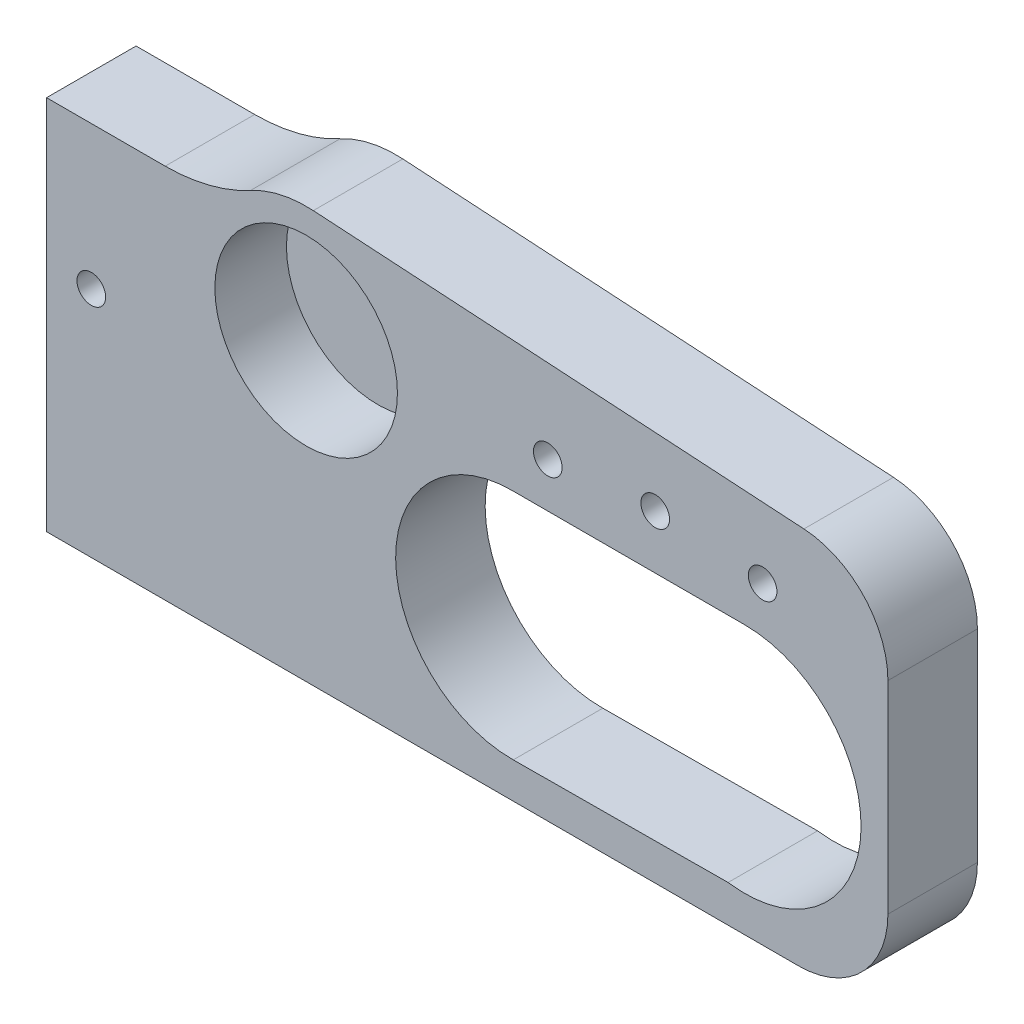
SolidWorks part; units mm, degrees
ref_plane "Front Plane" through (0, 0, 0) normal (1, 0, 0) x (0, 1, 0)
ref_plane "Top Plane" through (0, 0, 0) normal (0, 0, 1) x (0, 1, 0)
ref_plane "Right Plane" through (0, 0, 0) normal (0, 1, 0) x (-1, 0, 0)
sketch "Sketch1" plane through (0, 0, 0) normal (0, 0, 1) x (0, 1, 0)
  line L0 (12.9142, -18.3709) -> (14.6113, 9.0364)
  line L1 (7.9237, -23.0618) -> (-3.3763, -23.0618)
  line L4 (-8.3763, 23.9382) -> (12.6237, 23.9382)
  line L5 (12.6237, 23.9382) -> (12.6237, 17.3122)
  line L7 (-6.3763, -2.0618) -> (-6.2989, -16.0618)
  line L8 (6.6237, -15.0618) -> (6.6237, -2.0618)
  line L10 (-8.3763, 23.9382) -> (-8.3763, -18.0618)
  arc A2 (14.6113, 9.0364) -> (13.8358, 12.54) centre (8.1237, 9.4382) ccw
  arc A3 (12.6237, 17.3122) -> (13.8358, 12.54) centre (22.6237, 17.3122) ccw
  arc A4 (-8.3763, -18.0618) -> (-3.3763, -23.0618) centre (-3.3763, -18.0618) ccw
  arc A5 (7.9237, -23.0618) -> (12.9142, -18.3709) centre (7.9237, -18.0618) ccw
  circle A8 centre (4.6237, 21.4382) radius 0.8
  circle A9 centre (9.1237, -4.0618) radius 0.8
  circle A10 centre (9.6237, -10.0618) radius 0.8
  circle A11 centre (9.1237, -16.0618) radius 0.8
  arc A12 (6.6237, -2.0618) -> (-6.3759, -2.1337) centre (0.1237, -2.0618) ccw
  arc A13 (-6.3096, -14.1329) -> (6.6237, -15.0618) centre (0.1237, -15.0618) ccw
  circle A16 centre (8.1237, 9.4382) radius 5.1
  dimension "D8" = 2.5
  dimension "D1" = 21
  dimension "D2" = 42
  dimension "D3" = 27.4598
  dimension "D4" = 11.3
  dimension "D5" = 2.5
  dimension "D6" = 2.5
  dimension "D7" = 3
extrude "Boss-Extrude1" add sketch "Sketch1" along normal blind 5
sketch "Sketch2" plane through (-23.9382, 0, 0) normal (-1, 0, 0) x (0, -1, 0)
  line L0 (-12.6237, 2.5) -> (-9.6237, 2.5) construction
  line L1 (-12.6237, 5) -> (-12.6237, 0) construction
  line L2 (8.3763, 5) -> (8.3763, 0) construction
  circle A0 centre (-9.6237, 2.5) radius 1.25
  circle A1 centre (5.3763, 2.5) radius 1.25
  dimension "D2" = 3
  dimension "D3" = 2.5
  dimension "D4" = 2.5
  dimension "D1" = 3
  dimension "D5" = 0
extrude "Cut-Extrude1" cut sketch "Sketch2" against normal blind 5
sketch "Sketch21" plane through (0, 0, 0) normal (0, 0, -1) x (1, 0, 0)
  circle A0 centre (-9.4382, -8.1237) radius 5.1
extrude "Boss-Extrude2" add sketch "Sketch21" against normal blind 1
